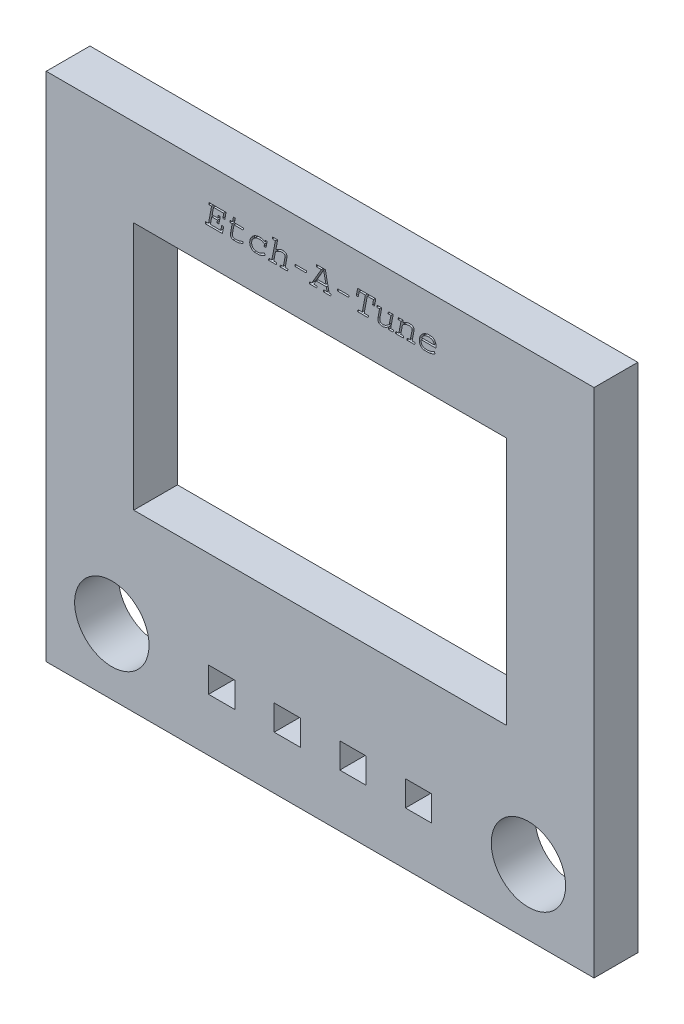
SolidWorks part; units mm, degrees
ref_plane "Front Plane" through (0, 0, 0) normal (0, 0, 1) x (1, 0, 0)
ref_plane "Top Plane" through (0, 0, 0) normal (0, 1, 0) x (1, 0, 0)
ref_plane "Right Plane" through (0, 0, 0) normal (1, 0, 0) x (0, 0, -1)
sketch "Sketch1" plane through (0, 0, 0) normal (0, 0, 1) x (1, 0, 0)
  line L0 (-10.5, -50.54) -> (-10.5, -56.34)
  line L1 (-42.61, -28.44) -> (42.61, -28.44)
  line L2 (-42.61, -28.44) -> (-42.61, 28.44)
  line L3 (-42.61, 28.44) -> (42.61, 28.44)
  line L4 (42.61, -28.44) -> (42.61, 28.44)
  line L5 (-42.61, -28.44) -> (42.61, 28.44) construction
  line L6 (-42.61, 28.44) -> (42.61, -28.44) construction
  line L7 (-62.61, 48.44) -> (62.61, 48.44)
  line L8 (-62.61, 48.44) -> (-62.61, -68.44)
  line L9 (-62.61, -68.44) -> (62.61, -68.44)
  line L10 (62.61, 48.44) -> (62.61, -68.44)
  line L11 (-25.5, -50.54) -> (-19.5, -50.54)
  line L12 (-25.5, -50.54) -> (-25.5, -56.34)
  line L13 (-25.5, -56.34) -> (-19.5, -56.34)
  line L14 (-19.5, -50.54) -> (-19.5, -56.34)
  line L15 (-47.61, -53.44) -> (47.61, -53.44) construction
  line L16 (-10.5, -50.54) -> (-4.5, -50.54)
  line L17 (-4.5, -50.54) -> (-4.5, -56.34)
  line L18 (-10.5, -56.34) -> (-4.5, -56.34)
  line L19 (4.5, -50.54) -> (4.5, -56.34)
  line L20 (4.5, -50.54) -> (10.5, -50.54)
  line L21 (10.5, -50.54) -> (10.5, -56.34)
  line L22 (4.5, -56.34) -> (10.5, -56.34)
  line L23 (19.5, -50.54) -> (19.5, -56.34)
  line L24 (19.5, -50.54) -> (25.5, -50.54)
  line L25 (25.5, -50.54) -> (25.5, -56.34)
  line L26 (19.5, -56.34) -> (25.5, -56.34)
  line L27 (-4.5, -53.44) -> (4.5, -53.44) construction
  line L28 (0, -68.44) -> (0, -53.44) construction
  line L29 (-4.5, -53.44) -> (4.5, -53.44) construction
  circle A0 centre (-47.61, -53.44) radius 8.5
  circle A1 centre (47.61, -53.44) radius 8.5
  point P0 (0, 0)
  point P16 (-25.5, -53.44)
  dimension "D12" = 17
  dimension "D13" = 17
  dimension "D1" = 56.88
  dimension "D2" = 85.22
  dimension "D3" = 20
  dimension "D4" = 20
  dimension "D5" = 125.22
  dimension "D6" = 20
  dimension "D7" = 40
  dimension "D8" = 15
  dimension "D9" = 15
  dimension "D10" = 15
  dimension "D11" = 15
  dimension "D14" = 6
  dimension "D15" = 5.8
  dimension "D16" = 4
extrude "Boss-Extrude1" add sketch "Sketch1" along normal blind 10
sketch "Sketch3" plane through (0, 0, 10) normal (0, 0, 1) x (1, 0, 0)
  line L0 (-62.61, 36.44) -> (62.61, 36.44) construction
  line L4 (-62.61, 48.44) -> (-62.61, -68.44)
  line L5 (-62.61, -68.44) -> (62.61, -68.44)
  line L6 (62.61, -68.44) -> (62.61, 48.44)
  line L7 (62.61, 48.44) -> (-62.61, 48.44)
  line L11 (62.61, 48.44) -> (-62.61, 48.44)
  line L13 (-22.3421, 36.4447) -> (-22.0427, 37.9911)
  line L14 (-62.61, 48.44) -> (-62.61, -68.44) construction
  line L15 (-62.61, -68.44) -> (62.61, -68.44) construction
  line L16 (-22.0427, 37.9911) -> (-22.4877, 37.9911)
  line L17 (-22.4877, 37.9911) -> (-22.6981, 36.8836)
  line L18 (-22.6981, 36.8836) -> (-25.0853, 36.8836)
  line L19 (-25.0853, 36.8836) -> (-24.7697, 38.5367)
  line L20 (-24.7697, 38.5367) -> (-23.475, 38.5367)
  line L21 (-23.475, 38.5367) -> (-23.5883, 37.9423)
  line L22 (-23.5883, 37.9423) -> (-23.1432, 37.9423)
  line L23 (-23.1432, 37.9423) -> (-22.8276, 39.5753)
  line L24 (-22.8276, 39.5753) -> (-23.2727, 39.5753)
  line L25 (-23.2727, 39.5753) -> (-23.3859, 38.9756)
  line L26 (-23.3859, 38.9756) -> (-24.6807, 38.9756)
  line L27 (-24.6807, 38.9756) -> (-24.3651, 40.6287)
  line L28 (-24.3651, 40.6287) -> (-22.0265, 40.6287)
  line L29 (-22.0265, 40.6287) -> (-22.2369, 39.5267)
  line L30 (-22.2369, 39.5267) -> (-21.7918, 39.5267)
  line L31 (-21.7918, 39.5267) -> (-21.4922, 41.0676)
  line L32 (-21.4922, 41.0676) -> (-25.3685, 41.0676)
  line L33 (-25.3685, 41.0676) -> (-25.4575, 40.6287)
  line L34 (-25.4575, 40.6287) -> (-24.8021, 40.6287)
  line L35 (-24.8021, 40.6287) -> (-25.5223, 36.8836)
  line L36 (-25.5223, 36.8836) -> (-26.1615, 36.8836)
  line L37 (-26.1615, 36.8836) -> (-26.2506, 36.4447)
  line L38 (-26.2506, 36.4447) -> (-22.3421, 36.4447)
  line L39 (-17.6286, 36.8169) -> (-17.5964, 37.2507)
  line L40 (-20.0422, 37.6121) -> (-19.6702, 39.508)
  line L41 (-19.6702, 39.508) -> (-17.5883, 39.508)
  line L42 (-17.5883, 39.508) -> (-17.5076, 39.9469)
  line L43 (-17.5076, 39.9469) -> (-19.5895, 39.9469)
  line L44 (-19.5895, 39.9469) -> (-19.3878, 40.9879)
  line L45 (-19.3878, 40.9879) -> (-19.8235, 40.9879)
  line L46 (-19.8235, 40.9879) -> (-20.0252, 39.9469)
  line L47 (-20.0252, 39.9469) -> (-20.561, 39.9469)
  line L48 (-20.561, 39.9469) -> (-20.6417, 39.508)
  line L49 (-20.6417, 39.508) -> (-20.1028, 39.508)
  line L50 (-20.1028, 39.508) -> (-20.4822, 37.4194)
  line L51 (-17.6292, 36.8159) -> (-17.6286, 36.8169)
  line L52 (-12.6072, 37.0061) -> (-12.696, 37.4435)
  line L53 (-12.7132, 39.1846) -> (-12.817, 38.6362)
  line L54 (-12.817, 38.6362) -> (-12.3732, 38.6362)
  line L55 (-12.3732, 38.6362) -> (-12.0988, 40.0216)
  line L56 (-12.0988, 40.0216) -> (-12.5427, 40.0216)
  line L57 (-12.5427, 40.0216) -> (-12.6153, 39.6454)
  line L58 (-12.6081, 37.005) -> (-12.6072, 37.0061)
  line L59 (-7.443, 36.4447) -> (-7.3542, 36.8836)
  line L60 (-7.3542, 36.8836) -> (-7.9893, 36.8836)
  line L61 (-7.9893, 36.8836) -> (-7.6185, 38.9179)
  line L62 (-10.118, 39.3655) -> (-9.7056, 41.5159)
  line L63 (-9.7056, 41.5159) -> (-10.8272, 41.5159)
  line L64 (-10.8272, 41.5159) -> (-10.916, 41.077)
  line L65 (-10.916, 41.077) -> (-10.2301, 41.077)
  line L66 (-10.2301, 41.077) -> (-11.037, 36.8836)
  line L67 (-11.037, 36.8836) -> (-11.7068, 36.8836)
  line L68 (-11.7068, 36.8836) -> (-11.7955, 36.4447)
  line L69 (-11.7955, 36.4447) -> (-10.0203, 36.4447)
  line L70 (-10.0203, 36.4447) -> (-9.9315, 36.8836)
  line L71 (-9.9315, 36.8836) -> (-10.6013, 36.8836)
  line L72 (-10.6013, 36.8836) -> (-10.214, 38.8858)
  line L73 (-8.0599, 38.741) -> (-8.4226, 36.8836)
  line L74 (-8.4226, 36.8836) -> (-9.0842, 36.8836)
  line L75 (-9.0842, 36.8836) -> (-9.173, 36.4447)
  line L76 (-9.173, 36.4447) -> (-7.443, 36.4447)
  line L77 (-3.1988, 38.2378) -> (-3.1101, 38.6768)
  line L78 (-3.1101, 38.6768) -> (-5.6922, 38.6768)
  line L79 (-5.6922, 38.6768) -> (-5.781, 38.2378)
  line L80 (-5.781, 38.2378) -> (-3.1988, 38.2378)
  line L81 (2.4097, 36.4447) -> (2.4983, 36.8836)
  line L82 (2.4983, 36.8836) -> (2.0632, 36.8836)
  line L83 (2.0632, 36.8836) -> (1.1928, 41.0676)
  line L84 (1.1928, 41.0676) -> (-0.7817, 41.0676)
  line L85 (-0.7817, 41.0676) -> (-0.8703, 40.6287)
  line L86 (-0.8703, 40.6287) -> (0.2821, 40.6287)
  line L87 (0.2821, 40.6287) -> (-1.91, 36.8836)
  line L88 (-1.91, 36.8836) -> (-2.4096, 36.8836)
  line L89 (-2.4096, 36.8836) -> (-2.4983, 36.4447)
  line L90 (-2.4983, 36.4447) -> (-0.7898, 36.4447)
  line L91 (-0.7898, 36.4447) -> (-0.7011, 36.8836)
  line L92 (-0.7011, 36.8836) -> (-1.4345, 36.8836)
  line L93 (-1.4345, 36.8836) -> (-0.9106, 37.7895)
  line L94 (-0.9106, 37.7895) -> (1.4184, 37.7895)
  line L95 (1.4184, 37.7895) -> (1.6038, 36.8836)
  line L96 (1.6038, 36.8836) -> (0.814, 36.8836)
  line L97 (0.814, 36.8836) -> (0.7253, 36.4447)
  line L98 (0.7253, 36.4447) -> (2.4097, 36.4447)
  line L99 (1.3298, 38.2285) -> (-0.6447, 38.2285)
  line L100 (-0.6447, 38.2285) -> (0.7979, 40.7781)
  line L101 (0.7979, 40.7781) -> (1.3298, 38.2285)
  line L102 (6.5141, 38.2378) -> (6.6029, 38.6768)
  line L103 (6.6029, 38.6768) -> (4.0207, 38.6768)
  line L104 (4.0207, 38.6768) -> (3.9319, 38.2378)
  line L105 (3.9319, 38.2378) -> (6.5141, 38.2378)
  line L106 (12.4179, 39.4451) -> (12.7326, 41.0676)
  line L107 (12.7326, 41.0676) -> (8.5769, 41.0676)
  line L108 (8.5769, 41.0676) -> (8.2622, 39.4451)
  line L109 (8.2622, 39.4451) -> (8.706, 39.4451)
  line L110 (8.706, 39.4451) -> (8.932, 40.6287)
  line L111 (8.932, 40.6287) -> (10.3441, 40.6287)
  line L112 (10.3441, 40.6287) -> (9.6259, 36.8836)
  line L113 (9.6259, 36.8836) -> (8.6334, 36.8836)
  line L114 (8.6334, 36.8836) -> (8.5446, 36.4447)
  line L115 (8.5446, 36.4447) -> (10.9735, 36.4447)
  line L116 (10.9735, 36.4447) -> (11.0623, 36.8836)
  line L117 (11.0623, 36.8836) -> (10.0697, 36.8836)
  line L118 (10.0697, 36.8836) -> (10.7879, 40.6287)
  line L119 (10.7879, 40.6287) -> (12.2, 40.6287)
  line L120 (12.2, 40.6287) -> (11.9741, 39.4451)
  line L121 (11.9741, 39.4451) -> (12.4179, 39.4451)
  line L122 (16.689, 36.4447) -> (16.7778, 36.8836)
  line L123 (16.7778, 36.8836) -> (16.1161, 36.8836)
  line L124 (16.1161, 36.8836) -> (16.7052, 39.9469)
  line L125 (16.7052, 39.9469) -> (15.5997, 39.9469)
  line L126 (15.5997, 39.9469) -> (15.519, 39.508)
  line L127 (15.519, 39.508) -> (16.1887, 39.508)
  line L128 (16.1887, 39.508) -> (15.8014, 37.5606)
  line L129 (13.6623, 37.7288) -> (14.0907, 39.9469)
  line L130 (14.0907, 39.9469) -> (13.0304, 39.9469)
  line L131 (13.0304, 39.9469) -> (12.9497, 39.508)
  line L132 (12.9497, 39.508) -> (13.5796, 39.508)
  line L133 (13.5796, 39.508) -> (13.2211, 37.5125)
  line L134 (15.6959, 37.0074) -> (15.5916, 36.4447)
  line L135 (15.5916, 36.4447) -> (16.689, 36.4447)
  line L136 (21.6096, 36.4447) -> (21.6984, 36.8836)
  line L137 (21.6984, 36.8836) -> (21.0367, 36.8836)
  line L138 (21.0367, 36.8836) -> (21.4321, 38.9637)
  line L139 (18.9133, 39.4134) -> (19.0113, 39.9469)
  line L140 (19.0113, 39.9469) -> (17.9058, 39.9469)
  line L141 (17.9058, 39.9469) -> (17.817, 39.508)
  line L142 (17.817, 39.508) -> (18.4868, 39.508)
  line L143 (18.4868, 39.508) -> (17.9865, 36.8836)
  line L144 (17.9865, 36.8836) -> (17.3168, 36.8836)
  line L145 (17.3168, 36.8836) -> (17.228, 36.4447)
  line L146 (17.228, 36.4447) -> (19.0032, 36.4447)
  line L147 (19.0032, 36.4447) -> (19.092, 36.8836)
  line L148 (19.092, 36.8836) -> (18.4222, 36.8836)
  line L149 (18.4222, 36.8836) -> (18.8176, 38.9259)
  line L150 (20.996, 38.9254) -> (20.601, 36.8836)
  line L151 (20.601, 36.8836) -> (19.9393, 36.8836)
  line L152 (19.9393, 36.8836) -> (19.8505, 36.4447)
  line L153 (19.8505, 36.4447) -> (21.6096, 36.4447)
  line L154 (26.23, 36.8799) -> (26.1735, 37.3077)
  line L155 (23.1114, 38.0977) -> (23.1276, 38.1631)
  line L156 (23.1276, 38.1631) -> (26.4317, 38.1631)
  line L157 (26.2295, 36.8789) -> (26.23, 36.8799)
  line L158 (26.0444, 38.6021) -> (23.2324, 38.6021)
  line L159 (26.0439, 38.6021) -> (26.0444, 38.6021)
  spline S0 degree 3 poles (-17.5964, 37.2507) (-17.72, 37.2025) (-17.9128, 37.1332) (-18.1784, 37.041) (-18.3916, 36.9671) (-18.6102, 36.9016) (-18.8982, 36.8364) (-19.1155, 36.8124) (-19.2589, 36.8089) knots 0 0 0 0 0.230271 0.355424 0.488042 0.621808 0.751238 1 1 1 1
  spline S1 degree 3 poles (-19.2589, 36.8089) (-19.3647, 36.8062) (-19.5794, 36.822) (-19.7791, 36.9025) (-19.873, 36.9525) knots 0 0 0 0 0.499018 1 1 1 1
  spline S2 degree 3 poles (-19.873, 36.9525) (-19.9214, 36.9825) (-19.9831, 37.044) (-20.0342, 37.1478) (-20.0769, 37.3284) (-20.0651, 37.4884) (-20.0422, 37.6121) knots 0 0 0 0 0.235222 0.352053 0.475254 1 1 1 1
  spline S3 degree 3 poles (-20.4822, 37.4194) (-20.4973, 37.3194) (-20.5045, 37.1744) (-20.485, 36.9909) (-20.4544, 36.8744) (-20.4095, 36.7714) (-20.3473, 36.6836) (-20.2713, 36.6087) (-20.1496, 36.5347) (-19.9902, 36.4655) (-19.7423, 36.3832) (-19.5511, 36.3646) (-19.4282, 36.37) knots 0 0 0 0 0.171925 0.245945 0.313097 0.376244 0.436146 0.495163 0.556527 0.677172 0.79049 1 1 1 1
  spline S4 degree 3 poles (-19.4282, 36.37) (-19.276, 36.3717) (-19.0466, 36.394) (-18.7422, 36.4501) (-18.2887, 36.5713) (-17.9196, 36.7023) (-17.6292, 36.8159) knots 0 0 0 0 0.24478 0.370352 0.497835 1 1 1 1
  spline S5 degree 3 poles (-12.696, 37.4435) (-12.7796, 37.3794) (-12.927, 37.2872) (-13.147, 37.1621) (-13.3524, 37.0548) (-13.5768, 36.9529) (-13.8953, 36.8516) (-14.1436, 36.8141) (-14.3102, 36.8066) knots 0 0 0 0 0.179376 0.29615 0.431466 0.574347 0.715767 1 1 1 1
  spline S6 degree 3 poles (-14.3102, 36.8066) (-14.4502, 36.8126) (-14.6515, 36.8315) (-14.9012, 36.8932) (-15.0596, 36.9499) (-15.1973, 37.021) (-15.3151, 37.1055) (-15.4119, 37.2047) (-15.4844, 37.3181) (-15.5399, 37.436) (-15.5869, 37.5526) (-15.6239, 37.6675) (-15.6487, 37.7812) (-15.6614, 37.8939) (-15.6646, 38.0417) (-15.6516, 38.1516) (-15.6341, 38.2226) knots 0 0 0 0 0.185137 0.2656 0.338874 0.406637 0.469503 0.529431 0.588401 0.646053 0.701365 0.754152 0.805121 0.854745 0.903544 1 1 1 1
  spline S7 degree 3 poles (-15.6341, 38.2226) (-15.6152, 38.313) (-15.5762, 38.4461) (-15.4992, 38.6139) (-15.4299, 38.7343) (-15.3501, 38.8501) (-15.26, 38.9621) (-15.1566, 39.0676) (-15.0442, 39.1691) (-14.9223, 39.2621) (-14.7926, 39.3445) (-14.6547, 39.413) (-14.5112, 39.4722) (-14.3597, 39.5173) (-14.1455, 39.5633) (-13.9792, 39.5785) (-13.8666, 39.5815) knots 0 0 0 0 0.115015 0.172081 0.229638 0.287876 0.347173 0.408555 0.471737 0.535745 0.599377 0.662915 0.727297 0.792645 0.859599 1 1 1 1
  spline S8 degree 3 poles (-13.8666, 39.5815) (-13.7542, 39.585) (-13.5885, 39.5755) (-13.3748, 39.5367) (-13.226, 39.493) (-13.0849, 39.4372) (-12.9078, 39.3427) (-12.7869, 39.2526) (-12.7132, 39.1846) knots 0 0 0 0 0.26931 0.396464 0.519857 0.640418 0.759764 1 1 1 1
  spline S9 degree 3 poles (-12.6153, 39.6454) (-12.6941, 39.7049) (-12.8181, 39.7878) (-12.9975, 39.873) (-13.1387, 39.9264) (-13.2871, 39.9664) (-13.4969, 40.0082) (-13.6596, 40.0196) (-13.7697, 40.0205) knots 0 0 0 0 0.23988 0.360255 0.481277 0.605674 0.732716 1 1 1 1
  spline S10 degree 3 poles (-13.7697, 40.0205) (-13.9348, 40.0137) (-14.1769, 39.9898) (-14.4849, 39.9185) (-14.6955, 39.8493) (-14.8912, 39.7647) (-15.0712, 39.6615) (-15.2384, 39.5446) (-15.3861, 39.4078) (-15.5199, 39.2653) (-15.641, 39.1213) (-15.7475, 38.9769) (-15.8389, 38.8315) (-15.9167, 38.6863) (-15.9999, 38.4946) (-16.0419, 38.3457) (-16.059, 38.246) knots 0 0 0 0 0.158336 0.232206 0.302459 0.370395 0.436001 0.500954 0.565343 0.628364 0.688164 0.745496 0.800101 0.852461 0.903216 1 1 1 1
  spline S11 degree 3 poles (-16.059, 38.246) (-16.0802, 38.1071) (-16.1029, 37.9029) (-16.0879, 37.6384) (-16.0606, 37.4586) (-16.0145, 37.2908) (-15.9479, 37.1363) (-15.8652, 36.993) (-15.7615, 36.8654) (-15.6443, 36.7508) (-15.5161, 36.6501) (-15.3766, 36.5657) (-15.228, 36.4947) (-15.0673, 36.4415) (-14.8351, 36.3874) (-14.6524, 36.3722) (-14.5285, 36.3711) knots 0 0 0 0 0.149284 0.216679 0.280615 0.341916 0.400732 0.45865 0.516805 0.574608 0.632251 0.689318 0.747305 0.806575 0.868462 1 1 1 1
  spline S12 degree 3 poles (-14.5285, 36.3711) (-14.3477, 36.3732) (-14.0797, 36.3933) (-13.7353, 36.4699) (-13.4916, 36.5463) (-13.2581, 36.6402) (-12.9586, 36.7844) (-12.7442, 36.9106) (-12.6081, 37.005) knots 0 0 0 0 0.26442 0.390771 0.514663 0.637126 0.758167 1 1 1 1
  spline S13 degree 3 poles (-7.6185, 38.9179) (-7.5885, 39.0434) (-7.5708, 39.2357) (-7.6089, 39.4856) (-7.6571, 39.6325) (-7.7162, 39.741) (-7.7786, 39.8128) (-7.8578, 39.872) (-7.9506, 39.9245) (-8.0612, 39.9629) (-8.2375, 40.0057) (-8.3806, 40.0161) (-8.4801, 40.0205) knots 0 0 0 0 0.22949 0.338714 0.447696 0.502544 0.557488 0.615208 0.677784 0.746307 0.822506 1 1 1 1
  spline S14 degree 3 poles (-8.4801, 40.0205) (-8.6233, 40.0168) (-8.8396, 39.9923) (-9.1209, 39.9122) (-9.3309, 39.8298) (-9.5372, 39.7322) (-9.8047, 39.5844) (-9.9965, 39.4587) (-10.118, 39.3655) knots 0 0 0 0 0.239739 0.362218 0.488616 0.616811 0.743905 1 1 1 1
  spline S15 degree 3 poles (-10.214, 38.8858) (-10.0999, 38.9767) (-9.92, 39.1026) (-9.6697, 39.2561) (-9.4776, 39.3652) (-9.2803, 39.4565) (-9.0183, 39.5473) (-8.8149, 39.5777) (-8.6809, 39.5815) knots 0 0 0 0 0.255522 0.384465 0.514872 0.642476 0.76502 1 1 1 1
  spline S16 degree 3 poles (-8.6809, 39.5815) (-8.6082, 39.5806) (-8.5045, 39.5724) (-8.3761, 39.5429) (-8.2963, 39.5153) (-8.2271, 39.4806) (-8.1703, 39.4368) (-8.1245, 39.386) (-8.0811, 39.3073) (-8.0477, 39.1972) (-8.0199, 38.9998) (-8.0371, 38.8447) (-8.0599, 38.741) knots 0 0 0 0 0.17174 0.244386 0.310633 0.370623 0.4263 0.479018 0.530865 0.637194 0.748537 1 1 1 1
  spline S17 degree 3 poles (15.8014, 37.5606) (15.7042, 37.4568) (15.5458, 37.3152) (15.3204, 37.1459) (15.1466, 37.0313) (14.9671, 36.9341) (14.7197, 36.8425) (14.5262, 36.8084) (14.3966, 36.8066) knots 0 0 0 0 0.260632 0.389185 0.51715 0.642384 0.762836 1 1 1 1
  spline S18 degree 3 poles (14.3966, 36.8066) (14.2885, 36.8062) (14.0803, 36.8289) (13.8866, 36.912) (13.8082, 36.9747) knots 0 0 0 0 0.52092 1 1 1 1
  spline S19 degree 3 poles (13.8082, 36.9747) (13.7609, 37.0177) (13.7038, 37.0953) (13.6552, 37.2141) (13.6381, 37.3106) (13.6318, 37.4112) (13.6334, 37.5518) (13.6469, 37.6582) (13.6623, 37.7288) knots 0 0 0 0 0.237353 0.354638 0.475944 0.601115 0.730347 1 1 1 1
  spline S20 degree 3 poles (13.2211, 37.5125) (13.2056, 37.4318) (13.1918, 37.3103) (13.1944, 37.1494) (13.2083, 37.0335) (13.2342, 36.9223) (13.2908, 36.7826) (13.3593, 36.692) (13.4101, 36.6373) knots 0 0 0 0 0.264502 0.392316 0.517255 0.639713 0.758831 1 1 1 1
  spline S21 degree 3 poles (13.4101, 36.6373) (13.4582, 36.5884) (13.5428, 36.5284) (13.6674, 36.4651) (13.7702, 36.43) (13.8786, 36.4034) (14.031, 36.3785) (14.1481, 36.3704) (14.2273, 36.3711) knots 0 0 0 0 0.232387 0.350882 0.474488 0.601408 0.730344 1 1 1 1
  spline S22 degree 3 poles (14.2273, 36.3711) (14.3147, 36.3641) (14.4532, 36.3798) (14.6465, 36.4195) (14.7828, 36.4597) (14.9012, 36.5019) (14.9973, 36.5453) (15.0993, 36.5988) (15.2079, 36.6599) (15.3209, 36.7336) (15.4875, 36.8458) (15.6111, 36.9413) (15.6959, 37.0074) knots 0 0 0 0 0.159896 0.254694 0.361791 0.420289 0.485171 0.555105 0.631531 0.713725 0.802641 1 1 1 1
  spline S23 degree 3 poles (21.4321, 38.9637) (21.4483, 39.0332) (21.4689, 39.1401) (21.4722, 39.2858) (21.4682, 39.3967) (21.4541, 39.506) (21.4077, 39.6411) (21.3501, 39.7305) (21.3019, 39.7811) knots 0 0 0 0 0.248919 0.376207 0.50625 0.634877 0.757713 1 1 1 1
  spline S24 degree 3 poles (21.3019, 39.7811) (21.2646, 39.818) (21.1983, 39.8662) (21.0985, 39.9186) (21.0115, 39.9555) (20.9128, 39.9844) (20.7566, 40.0138) (20.6315, 40.0197) (20.5442, 40.0205) knots 0 0 0 0 0.192799 0.299924 0.414972 0.540646 0.677887 1 1 1 1
  spline S25 degree 3 poles (20.5442, 40.0205) (20.403, 40.0185) (20.189, 39.9984) (19.9092, 39.9297) (19.6993, 39.8583) (19.4935, 39.7691) (19.2239, 39.6321) (19.034, 39.5059) (18.9133, 39.4134) knots 0 0 0 0 0.23953 0.362394 0.487754 0.614811 0.742248 1 1 1 1
  spline S26 degree 3 poles (18.8176, 38.9259) (18.9241, 39.0203) (19.0958, 39.1501) (19.3438, 39.2971) (19.5393, 39.3947) (19.7386, 39.4747) (19.9984, 39.5525) (20.1961, 39.5793) (20.3259, 39.5815) knots 0 0 0 0 0.254465 0.384045 0.515469 0.645171 0.767901 1 1 1 1
  spline S27 degree 3 poles (20.3259, 39.5815) (20.4155, 39.5849) (20.5494, 39.5739) (20.7183, 39.5214) (20.8161, 39.4745) (20.8873, 39.4264) (20.9305, 39.3789) (20.9639, 39.3235) (20.9908, 39.2605) (21.0047, 39.1879) (21.0147, 39.0753) (21.0055, 38.9862) (20.996, 38.9254) knots 0 0 0 0 0.239079 0.354241 0.469758 0.527036 0.582093 0.639381 0.698908 0.763606 0.835452 1 1 1 1
  spline S28 degree 3 poles (26.1735, 37.3077) (26.0068, 37.2243) (25.7593, 37.1103) (25.4269, 36.9916) (25.1958, 36.9224) (24.9789, 36.8725) (24.7302, 36.8231) (24.5517, 36.8076) (24.4399, 36.8066) knots 0 0 0 0 0.307566 0.448678 0.581916 0.705232 0.815644 1 1 1 1
  spline S29 degree 3 poles (24.4399, 36.8066) (24.2588, 36.8078) (24.0329, 36.8214) (23.7739, 36.8842) (23.6179, 36.9429) (23.5084, 37.0013) (23.4418, 37.0494) knots 0 0 0 0 0.521686 0.645105 0.764353 1 1 1 1
  spline S30 degree 3 poles (23.4418, 37.0494) (23.373, 37.098) (23.2881, 37.1962) (23.2001, 37.3496) (23.149, 37.4838) (23.1113, 37.6285) (23.0869, 37.835) (23.095, 37.9928) (23.1114, 38.0977) knots 0 0 0 0 0.217641 0.334392 0.459651 0.590529 0.723384 1 1 1 1
  spline S31 degree 3 poles (26.4317, 38.1631) (26.4564, 38.2843) (26.4812, 38.4649) (26.4831, 38.7023) (26.4697, 38.8698) (26.4387, 39.0295) (26.3954, 39.1827) (26.3328, 39.327) (26.2596, 39.4653) (26.1675, 39.5928) (26.0535, 39.7037) (25.9198, 39.7979) (25.766, 39.8747) (25.5932, 39.9366) (25.3255, 39.9989) (25.1118, 40.0162) (24.9641, 40.0205) knots 0 0 0 0 0.131929 0.193772 0.252919 0.310795 0.367008 0.422433 0.478148 0.533685 0.589449 0.646913 0.707424 0.77228 0.842245 1 1 1 1
  spline S32 degree 3 poles (24.9641, 40.0205) (24.8301, 40.0176) (24.631, 40.0026) (24.3736, 39.9481) (24.188, 39.8951) (24.0095, 39.8243) (23.8367, 39.7401) (23.6709, 39.6401) (23.5113, 39.5278) (23.3624, 39.4022) (23.2259, 39.2651) (23.1047, 39.1167) (22.9973, 38.9578) (22.9055, 38.7882) (22.7989, 38.5451) (22.7435, 38.3512) (22.7168, 38.218) knots 0 0 0 0 0.128681 0.190871 0.252333 0.313715 0.374851 0.436663 0.499359 0.56191 0.623446 0.684755 0.745563 0.807236 0.869619 1 1 1 1
  spline S33 degree 3 poles (22.7168, 38.218) (22.6921, 38.1004) (22.6697, 37.9246) (22.671, 37.693) (22.6868, 37.5287) (22.7197, 37.3707) (22.768, 37.2189) (22.8311, 37.0735) (22.9103, 36.9349) (23.0079, 36.8068) (23.1279, 36.694) (23.2702, 36.5996) (23.4324, 36.5196) (23.6169, 36.4586) (23.9018, 36.3947) (24.1293, 36.3736) (24.287, 36.3711) knots 0 0 0 0 0.125287 0.18415 0.241266 0.297234 0.352182 0.407085 0.462371 0.518234 0.574521 0.633293 0.695745 0.762627 0.835499 1 1 1 1
  spline S34 degree 3 poles (24.287, 36.3711) (24.4535, 36.3718) (24.704, 36.3929) (25.0363, 36.4514) (25.2859, 36.5136) (25.5319, 36.5899) (25.8507, 36.7018) (26.081, 36.8039) (26.2295, 36.8789) knots 0 0 0 0 0.246516 0.371838 0.499517 0.627371 0.753387 1 1 1 1
  spline S35 degree 3 poles (23.2324, 38.6021) (23.2503, 38.6645) (23.2925, 38.7534) (23.3618, 38.8671) (23.4253, 38.9503) (23.4966, 39.0331) (23.5792, 39.112) (23.6701, 39.1903) (23.77, 39.2663) (23.8792, 39.3358) (23.9969, 39.3984) (24.123, 39.4519) (24.2578, 39.4962) (24.4007, 39.5312) (24.6067, 39.5656) (24.7664, 39.5783) (24.8753, 39.5815) knots 0 0 0 0 0.095333 0.144541 0.196185 0.249464 0.305464 0.364467 0.426326 0.490316 0.55526 0.62262 0.692119 0.76421 0.839302 1 1 1 1
  spline S36 degree 3 poles (24.8753, 39.5815) (24.998, 39.5769) (25.1731, 39.5563) (25.3916, 39.5075) (25.5286, 39.4605) (25.6476, 39.4043) (25.7474, 39.3355) (25.8302, 39.2575) (25.8897, 39.167) (25.9353, 39.0768) (25.9762, 38.9924) (26.0076, 38.9131) (26.0316, 38.8395) (26.0464, 38.7718) (26.0587, 38.6933) (26.0532, 38.6365) (26.0439, 38.6021) knots 0 0 0 0 0.211913 0.303701 0.386173 0.461625 0.530234 0.594877 0.656771 0.715998 0.769516 0.818691 0.863118 0.903068 0.938334 1 1 1 1
  dimension "D2" = 12
  dimension "D1" = 0
extrude "Cut-Extrude2" cut sketch "Sketch3" against normal blind 1 and the other way through all
